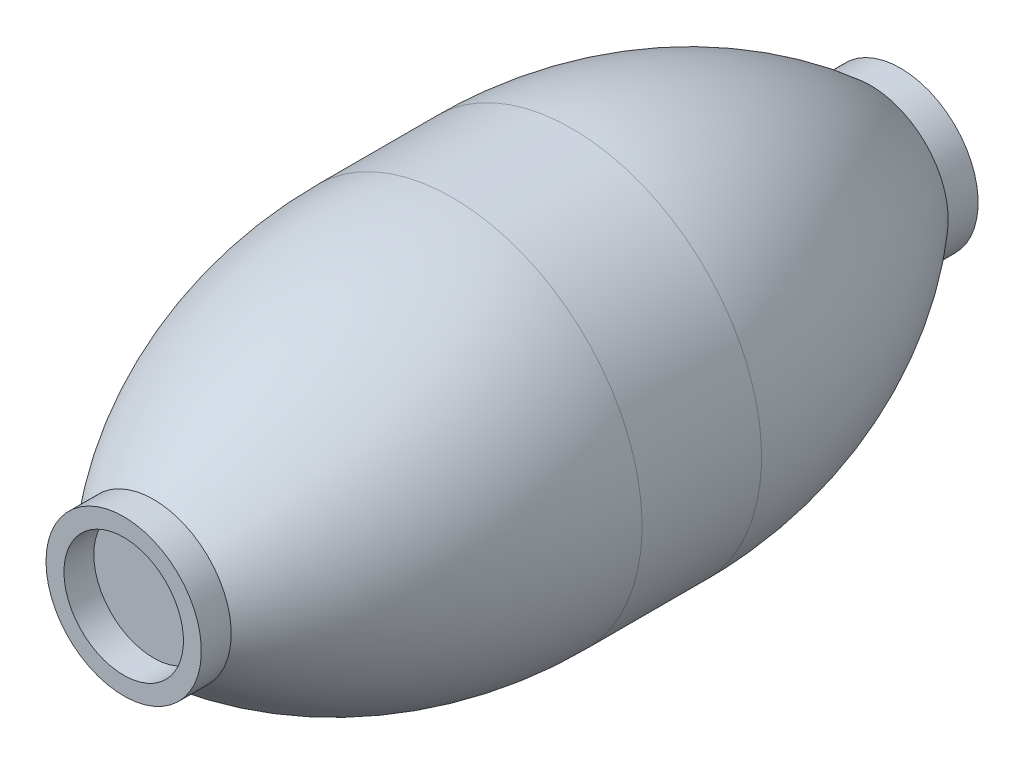
SolidWorks part; units mm, degrees
material "PVC 0.007 Plasticized"
ref_plane "Front Plane" through (0, 0, 0) normal (0, 0, 1) x (1, 0, 0)
ref_plane "Top Plane" through (0, 0, 0) normal (0, 1, 0) x (1, 0, 0)
ref_plane "Right Plane" through (0, 0, 0) normal (1, 0, 0) x (0, 0, -1)
sketch "Sketch2" plane through (0, 0, 0) normal (0, 1, 0) x (1, 0, 0)
  line L0 (0, 130) -> (0, -130) construction
  line L1 (-20, 130) -> (-20, 120)
  line L2 (-20, 120) -> (0, 120)
  line L3 (0, 120) -> (0, -120)
  line L4 (0, -120) -> (-20, -120)
  line L5 (-20, -120) -> (-20, -130)
  line L6 (-20, 130) -> (-26, 130)
  line L7 (-26, 130) -> (-26, 120)
  line L8 (-63.5, 20) -> (-63.5, -20)
  line L9 (0, 0) -> (-63.5, 0) construction
  line L10 (-20, -130) -> (-26, -130)
  line L11 (-26, -130) -> (-26, -120)
  arc A0 (-26, 120) -> (-63.5, 20) centre (88.5833, 20) ccw
  arc A1 (-26, -120) -> (-63.5, -20) centre (88.5833, -20) cw
  point P5 (-63.5, 0)
  dimension "D1" = 40
  dimension "D2" = 10
  dimension "D3" = 240
  dimension "D4" = 6
  dimension "D5" = 127
  dimension "D6" = 40
revolve "Revolve1" add sketch "Sketch2" angle 360 about L0
